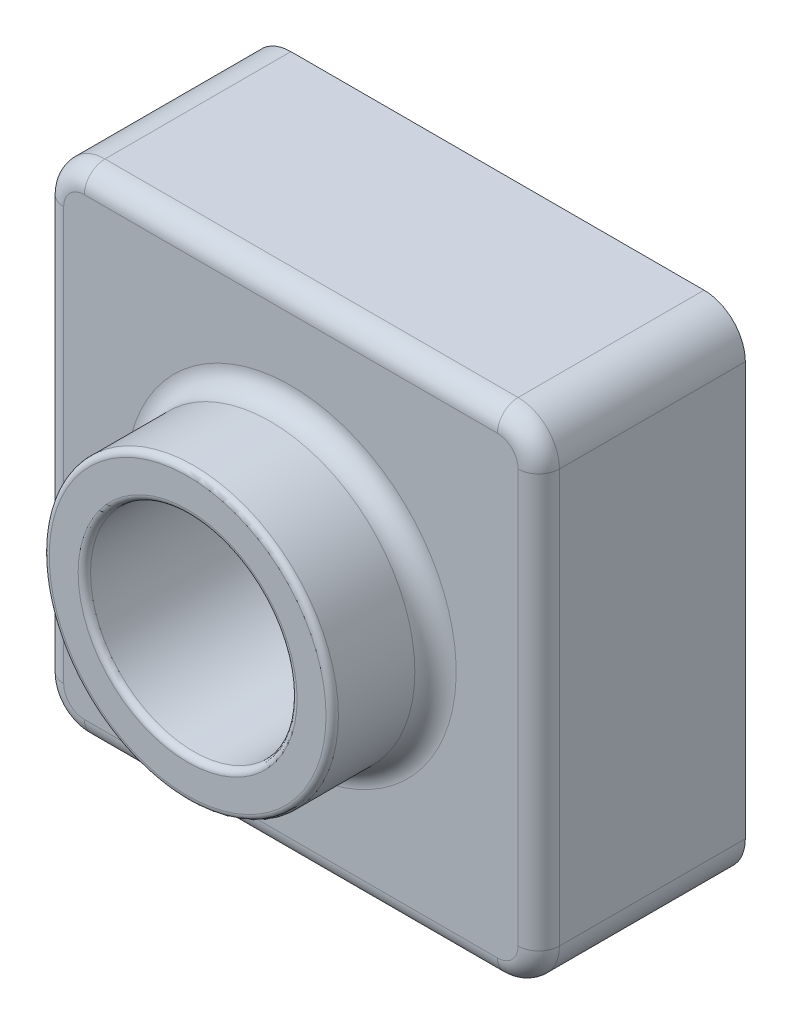
SolidWorks part; units mm, degrees
material "Chrome Stainless Steel"
ref_plane "Front" through (0, 0, 0) normal (0, 0, 1) x (1, 0, 0)
ref_plane "Top" through (0, 0, 0) normal (0, 1, 0) x (1, 0, 0)
ref_plane "Right" through (0, 0, 0) normal (1, 0, 0) x (0, 0, -1)
sketch "Sketch1" plane through (0, 0, 0) normal (0, 0, 1) x (1, 0, 0)
  line L1 (0, 0) -> (120, 0)
  line L2 (0, 0) -> (0, 120)
  line L3 (0, 120) -> (120, 120)
  line L4 (120, 0) -> (120, 120)
  dimension "D1" = 120
  dimension "D2" = 120
extrude "Boss-Extrude2" add sketch "Sketch1" along normal blind 50
sketch "Sketch2" plane through (0, 0, 50) normal (0, 0, 1) x (1, 0, 0)
  line L0 (0, 0) -> (120, 0) construction
  line L1 (0, 120) -> (0, 0) construction
  circle A0 centre (60, 60) radius 35
  dimension "D1" = 70
  dimension "D2" = 60
  dimension "D3" = 60
extrude "Boss-Extrude3" add sketch "Sketch2" along normal blind 25
sketch "Sketch3" plane through (0, 0, 75) normal (0, 0, 1) x (1, 0, 0)
  circle A0 centre (60, 60) radius 25
  circle A1 centre (60, 60) radius 35 construction
  dimension "D1" = 10
extrude "Cut-Extrude1" cut sketch "Sketch3" against normal through all
fillet "Fillet1" radius 10 4 edges at (0, 0, 25) (120, 0, 25) (0, 120, 25) (120, 120, 25)
fillet "Fillet2" radius 1.5 2 edges at (95, 60, 75) (85, 60, 75)
fillet "Fillet3" radius 5 9 edges at (25, 60, 50) (2.9289, 117.0711, 50) (60, 120, 50) (117.0711, 117.0711, 50) (120, 60, 50) (117.0711, 2.9289, 50) (60, 0, 50) (2.9289, 2.9289, 50) (0, 60, 50)
shell "Shell1" thickness 2
